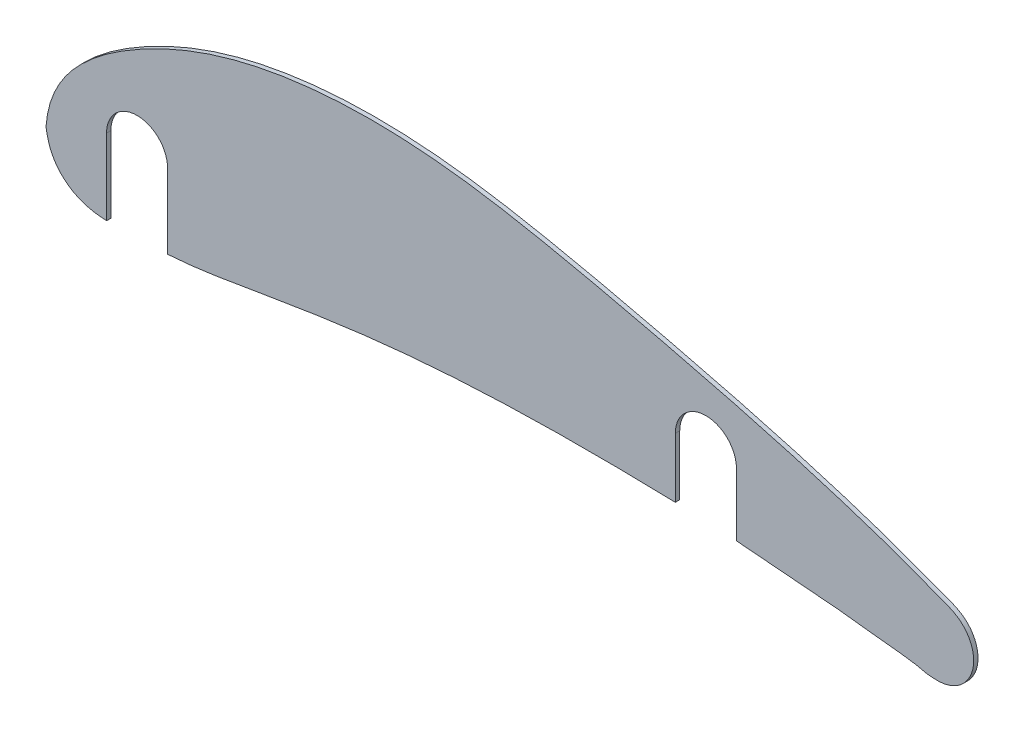
SolidWorks part; units mm, degrees
material "ABS"
ref_plane "Front Plane" through (0, 0, 0) normal (0, 0, 1) x (1, 0, 0)
ref_plane "Top Plane" through (0, 0, 0) normal (0, 1, 0) x (1, 0, 0)
ref_plane "Right Plane" through (0, 0, 0) normal (1, 0, 0) x (0, 0, -1)
sketch "Sketch1" plane through (0, 0, 0) normal (0, 0, 1) x (1, 0, 0)
  spline S0 degree 3 poles (0.0006, 0.0001) (0.8106, 7.3592) (8.6491, 17.8566) (26.2867, 29.9752) (52.1111, 42.0692) (89.5976, 49.2908) (131.4008, 47.8848) (173.2567, 40.0411) (217.9611, 29.613) (256.9521, 19.5289) (290.3598, 8.711) (301.2732, 4.3828) (314.8169, -0.5162) (309.8463, 0.0001) knots 0 0 0 0 0.060864 0.113688 0.188609 0.312909 0.448482 0.557612 0.691544 0.852438 0.929756 0.976058 1 1 1 1
  spline S1 degree 3 poles (309.8463, 0.0001) (303.9568, 1.471) (293.9895, 2.094) (276.264, 4.5144) (260.8463, 5.4274) (235.8588, 7.8703) (205.1014, 8.8381) (157.7186, 9.0307) (110.4973, 6.1815) (66.5062, -0.5867) (36.4547, -6.0985) (15.3166, -6.1891) (1.2307, -6.9241) (0.0006, 0.0001) knots 0 0 0 0 0.057787 0.095275 0.171021 0.205339 0.335319 0.464904 0.658702 0.785512 0.893517 0.943092 1 1 1 1
extrude "Boss-Extrude1" add sketch "Sketch1" along normal blind 1.5875
sketch "Sketch2" plane through (0, 0, 1.5875) normal (0, 0, 1) x (1, 0, 0)
  circle A1 centre (227.2963, 19.0501) radius 5
  circle A2 centre (20.32, 10.16) radius 5
  dimension "D3" = 10
  dimension "D6" = 20.32
  dimension "D8" = 10
  dimension "D1" = 82.55
  dimension "D4" = 19.05
  dimension "D5" = 10.16
extrude "Cut-Extrude1" cut sketch "Sketch2" against normal blind 4 contours A1
sketch "Sketch3" plane through (0, 0, 0) normal (0, 0, -1) x (-1, 0, 0)
  circle A0 centre (-227.2963, 19.0501) radius 5
  circle A1 centre (-20.32, 10.16) radius 5
  circle A2 centre (-227.2963, 19.0501) radius 5 construction
  circle A3 centre (-20.32, 10.16) radius 5 construction
  spline S5 degree 3 poles (-794.819, 3953.6372) (-366.3145, -67.9732) (-338.336, -19.8467) (-305.9476, -12.1233) (-305.5233, -12.0295) (-304.2487, -11.7666) (-303.3965, -11.6156) (-300.8352, -11.213) (-299.1211, -11.0104) (-295.689, -10.6461) (-293.9708, -10.4848) (-291.3954, -10.2247) (-290.5373, -10.1347) (-288.822, -9.9442) (-287.9649, -9.8444) (-285.3941, -9.5376) (-283.6812, -9.3228) (-280.254, -8.9085) (-278.5394, -8.7116) (-273.3892, -8.1853) (-269.9489, -7.9035) (-263.0656, -7.3675) (-259.6226, -7.1135) (-252.7436, -6.5343) (-249.3084, -6.2011) (-242.431, -5.6059) (-238.9878, -5.3542) (-232.0935, -4.9305) (-228.6415, -4.7575) (-218.2859, -4.3276) (-211.3818, -4.1597) (-197.5731, -3.918) (-190.6686, -3.8461) (-176.8592, -3.8453) (-169.9542, -3.9165) (-156.1436, -4.2469) (-149.2349, -4.5055) (-135.4369, -5.2363) (-128.547, -5.7084) (-114.7879, -6.8956) (-107.9189, -7.6126) (-94.2037, -9.3155) (-87.359, -10.2944) (-77.1158, -11.889) (-73.7047, -12.4417) (-66.8874, -13.5783) (-63.482, -14.1674) (-53.262, -15.9097) (-46.4424, -17.0289) (-37.8533, -17.9873) (-36.1323, -18.1567) (-32.6884, -18.4393) (-30.9647, -18.5506) (-25.7891, -18.7998) (-22.3328, -18.8616) (-18.0138, -18.9646) (-17.15, -18.9864) (-15.4226, -19.0355) (-14.559, -19.065) (-12.8314, -19.1079) (-11.9674, -19.1211) (-10.2388, -19.1103) (-9.3743, -19.0865) (-6.8, -18.9358) (-5.1041, -18.7297) (-2.6061, -18.1813) (-1.781, -17.9588) (-0.5569, -17.5549) (-0.1511, -17.4087) (0.6556, -17.0908) (1.0582, -16.9184) (3.0336, -15.9992) (4.4968, -15.0839) (6.1651, -13.6925) (6.4918, -13.4006) (7.122, -12.7971) (7.425, -12.4861) (8.2983, -11.5259) (8.8331, -10.8497) (9.5651, -9.782) (9.7973, -9.4172) (10.2382, -8.6696) (10.4474, -8.2857) (11.035, -7.1145) (11.3705, -6.3152) (11.9375, -4.6822) (12.169, -3.8486) (12.4425, -2.5739) (12.5175, -2.1436) (245.8962, 1311.483) (479.1987, 2624.6798) (712.5006, 3937.874) knots -0.290887 -0.290887 -0.290887 -0.290887 0.003906 0.003906 0.007812 0.007812 0.015625 0.015625 0.03125 0.03125 0.046875 0.046875 0.054687 0.054687 0.0625 0.0625 0.078125 0.078125 0.09375 0.09375 0.125 0.125 0.15625 0.15625 0.1875 0.1875 0.21875 0.21875 0.25 0.25 0.3125 0.3125 0.375 0.375 0.4375 0.4375 0.5 0.5 0.5625 0.5625 0.625 0.625 0.6875 0.6875 0.71875 0.71875 0.75 0.75 0.8125 0.8125 0.828125 0.828125 0.84375 0.84375 0.875 0.875 0.882812 0.882812 0.890625 0.890625 0.898438 0.898438 0.90625 0.90625 0.921875 0.921875 0.929687 0.929687 0.933594 0.933594 0.9375 0.9375 0.953125 0.953125 0.957031 0.957031 0.960938 0.960938 0.96875 0.96875 0.972656 0.972656 0.976563 0.976563 0.984375 0.984375 0.992188 0.992188 0.996094 0.996094 12.93108 12.93108 12.93108 12.93108 only from (-307.6407, -12.5391) to (12.8229, -0.4244)
  spline S6 degree 3 poles (450.4865, -3976.3582) (304.5409, -2650.5224) (158.5953, -1324.6865) (12.5919, 1.6739) (12.5289, 2.1971) (12.2979, 3.7557) (12.0986, 4.783) (11.3667, 7.8296) (10.7001, 9.8139) (9.6458, 12.2364) (9.4233, 12.7191) (8.9589, 13.6734) (8.2345, 15.0856) (7.4307, 16.4423) (5.7262, 19.088) (4.4608, 20.7616) (2.4032, 23.1605) (1.6888, 23.9434) (0.222, 25.4669) (-2.0301, 27.684) (-4.4106, 29.7332) (-9.3168, 33.6415) (-12.7815, 35.993) (-18.1647, 39.2766) (-19.9904, 40.3334) (-23.6661, 42.358) (-25.5203, 43.3273) (-31.1305, 46.109) (-34.9342, 47.7954) (-46.5315, 52.3626) (-54.5152, 54.7412) (-63.7448, 56.7617) (-64.7747, 56.9772) (-66.8348, 57.3892) (-69.9258, 57.9785) (-73.0196, 58.4848) (-79.2106, 59.3934) (-83.3425, 59.8608) (-95.7504, 60.8925) (-104.0386, 61.0863) (-116.492, 60.7375) (-120.6467, 60.5145) (-126.8836, 60.0306) (-128.9634, 59.8445) (-133.1246, 59.4241) (-135.2075, 59.1895) (-145.595, 57.9058) (-153.8328, 56.5247) (-166.1326, 54.1736) (-170.223, 53.3435) (-178.3938, 51.633) (-182.4737, 50.7513) (-194.7, 48.0394) (-202.8328, 46.1427) (-215.0143, 43.2113) (-219.0722, 42.221) (-227.1821, 40.2119) (-231.2322, 39.1918) (-243.362, 36.0642) (-251.4202, 33.8872) (-263.4483, 30.4288) (-267.4479, 29.2444) (-275.4266, 26.8089) (-279.4062, 25.5593) (-285.3572, 23.6252) (-287.3377, 22.9703) (-291.2905, 21.6338) (-293.2629, 20.9523) (-297.195, 19.5486) (-299.1532, 18.8211) (-303.0645, 17.3496) (-305.019, 16.6102) (-307.9551, 15.5148) (-308.9343, 15.1515) (-310.8939, 14.4286) (-311.8752, 14.0719) (-313.8314, 13.3379) (-314.808, 12.9614) (-316.7192, 12.1265) (-317.6523, 11.6639) (-318.978, 10.8209) (-319.4082, 10.5149) (-320.2258, 9.8596) (-320.6153, 9.5093) (-321.3536, 8.7611) (-321.6995, 8.3658) (-322.3367, 7.5434) (-322.6295, 7.1149) (-323.1632, 6.2229) (-323.4044, 5.7588) (-323.8312, 4.7968) (-324.1948, 3.8185) (-324.4364, 2.809) (-324.5716, 2.0401) (-324.6089, 1.7818) (-324.6679, 1.2612) (-324.6896, 0.9981) (-324.7567, -0.3109) (-324.6826, -1.3467) (-324.3823, -2.8833) (-324.249, -3.3956) (-323.9242, -4.3886) (-323.541, -5.3551) (-323.0431, -6.2692) (-322.6256, -6.9348) (-322.4785, -7.1539) (-322.1729, -7.5802) (-322.0142, -7.7878) (-321.1922, -8.7978) (-320.4439, -9.5189) (-318.7612, -10.7826) (-317.8577, -11.3014) (-316.4211, -11.9133) (-315.9254, -12.0903) (-314.9178, -12.3839) (-314.4094, -12.4998) (-313.384, -12.6741) (-312.867, -12.7323) (-311.8251, -12.7968) (-311.2988, -12.8028) (-310.2504, -12.7747) (-309.7275, -12.7412) (-275.8665, -9.8118) (-245.9968, 43.8257) (63.2429, -3989.5034) knots -9.868844 -9.868844 -9.868844 -9.868844 0.003906 0.003906 0.007813 0.007813 0.015625 0.015625 0.03125 0.03125 0.035156 0.035156 0.039063 0.046875 0.046875 0.0625 0.0625 0.070313 0.070313 0.078125 0.09375 0.09375 0.125 0.125 0.140625 0.140625 0.15625 0.15625 0.1875 0.1875 0.25 0.25 0.257813 0.257813 0.265625 0.28125 0.28125 0.3125 0.3125 0.375 0.375 0.40625 0.40625 0.421875 0.421875 0.4375 0.4375 0.5 0.5 0.53125 0.53125 0.5625 0.5625 0.625 0.625 0.65625 0.65625 0.6875 0.6875 0.75 0.75 0.78125 0.78125 0.8125 0.8125 0.828125 0.828125 0.84375 0.84375 0.859375 0.859375 0.875 0.875 0.882813 0.882813 0.890625 0.890625 0.898438 0.898438 0.90625 0.90625 0.910156 0.910156 0.914063 0.914063 0.917969 0.917969 0.921875 0.921875 0.925781 0.925781 0.929688 0.933594 0.933594 0.935547 0.935547 0.9375 0.9375 0.945313 0.945313 0.949219 0.949219 0.953125 0.957031 0.957031 0.958984 0.958984 0.960938 0.960938 0.96875 0.96875 0.976563 0.976563 0.980469 0.980469 0.984375 0.984375 0.988281 0.988281 0.992188 0.992188 0.996094 0.996094 1.245538 1.245538 1.245538 1.245538 only from (12.8229, -0.4244) to (-307.6407, -12.5391)
  spline S7 degree 3 poles (-307.6407, -12.5391) (-307.2176, -12.4334) (-306.7947, -12.3253) (-305.9476, -12.1233) (-305.5233, -12.0295) (-304.2487, -11.7666) (-303.3965, -11.6156) (-300.8352, -11.213) (-299.1211, -11.0104) (-295.689, -10.6461) (-293.9708, -10.4848) (-291.3954, -10.2247) (-290.5373, -10.1347) (-288.822, -9.9442) (-287.9649, -9.8444) (-285.3941, -9.5376) (-283.6812, -9.3228) (-280.254, -8.9085) (-278.5394, -8.7116) (-273.3892, -8.1853) (-269.9489, -7.9035) (-263.0656, -7.3675) (-259.6226, -7.1135) (-252.7436, -6.5343) (-249.3084, -6.2011) (-242.431, -5.6059) (-238.9878, -5.3542) (-232.0935, -4.9305) (-228.6415, -4.7575) (-218.2859, -4.3276) (-211.3818, -4.1597) (-197.5731, -3.918) (-190.6686, -3.8461) (-176.8592, -3.8453) (-169.9542, -3.9165) (-156.1436, -4.2469) (-149.2349, -4.5055) (-135.4369, -5.2363) (-128.547, -5.7084) (-114.7879, -6.8956) (-107.9189, -7.6126) (-94.2037, -9.3155) (-87.359, -10.2944) (-77.1158, -11.889) (-73.7047, -12.4417) (-66.8874, -13.5783) (-63.482, -14.1674) (-53.262, -15.9097) (-46.4424, -17.0289) (-37.8533, -17.9873) (-36.1323, -18.1567) (-32.6884, -18.4393) (-30.9647, -18.5506) (-25.7891, -18.7998) (-22.3328, -18.8616) (-18.0138, -18.9646) (-17.15, -18.9864) (-15.4226, -19.0355) (-14.559, -19.065) (-12.8314, -19.1079) (-11.9674, -19.1211) (-10.2388, -19.1103) (-9.3743, -19.0865) (-6.8, -18.9358) (-5.1041, -18.7297) (-2.6061, -18.1813) (-1.781, -17.9588) (-0.5569, -17.5549) (-0.1511, -17.4087) (0.6556, -17.0908) (1.0582, -16.9184) (3.0336, -15.9992) (4.4968, -15.0839) (6.1651, -13.6925) (6.4918, -13.4006) (7.122, -12.7971) (7.425, -12.4861) (8.2983, -11.5259) (8.8331, -10.8497) (9.5651, -9.782) (9.7973, -9.4172) (10.2382, -8.6696) (10.4474, -8.2857) (11.035, -7.1145) (11.3705, -6.3152) (11.9375, -4.6822) (12.169, -3.8486) (12.4425, -2.5739) (12.5175, -2.1436) (12.6702, -1.284) (12.7465, -0.8542) (12.8229, -0.4244) knots 0 0 0 0 0.003906 0.003906 0.007812 0.007812 0.015625 0.015625 0.03125 0.03125 0.046875 0.046875 0.054687 0.054687 0.0625 0.0625 0.078125 0.078125 0.09375 0.09375 0.125 0.125 0.15625 0.15625 0.1875 0.1875 0.21875 0.21875 0.25 0.25 0.3125 0.3125 0.375 0.375 0.4375 0.4375 0.5 0.5 0.5625 0.5625 0.625 0.625 0.6875 0.6875 0.71875 0.71875 0.75 0.75 0.8125 0.8125 0.828125 0.828125 0.84375 0.84375 0.875 0.875 0.882812 0.882812 0.890625 0.890625 0.898438 0.898438 0.90625 0.90625 0.921875 0.921875 0.929687 0.929687 0.933594 0.933594 0.9375 0.9375 0.953125 0.953125 0.957031 0.957031 0.960938 0.960938 0.96875 0.96875 0.972656 0.972656 0.976563 0.976563 0.984375 0.984375 0.992188 0.992188 0.996094 0.996094 1 1 1 1
  spline S8 degree 3 poles (12.8229, -0.4244) (12.7651, 0.1002) (12.7074, 0.6248) (12.5919, 1.6739) (12.5289, 2.1971) (12.2979, 3.7557) (12.0986, 4.783) (11.3667, 7.8296) (10.7001, 9.8139) (9.6458, 12.2364) (9.4233, 12.7191) (8.9589, 13.6734) (8.2345, 15.0856) (7.4307, 16.4423) (5.7262, 19.088) (4.4608, 20.7616) (2.4032, 23.1605) (1.6888, 23.9434) (0.222, 25.4669) (-2.0301, 27.684) (-4.4106, 29.7332) (-9.3168, 33.6415) (-12.7815, 35.993) (-18.1647, 39.2766) (-19.9904, 40.3334) (-23.6661, 42.358) (-25.5203, 43.3273) (-31.1305, 46.109) (-34.9342, 47.7954) (-46.5315, 52.3626) (-54.5152, 54.7412) (-63.7448, 56.7617) (-64.7747, 56.9772) (-66.8348, 57.3892) (-69.9258, 57.9785) (-73.0196, 58.4848) (-79.2106, 59.3934) (-83.3425, 59.8608) (-95.7504, 60.8925) (-104.0386, 61.0863) (-116.492, 60.7375) (-120.6467, 60.5145) (-126.8836, 60.0306) (-128.9634, 59.8445) (-133.1246, 59.4241) (-135.2075, 59.1895) (-145.595, 57.9058) (-153.8328, 56.5247) (-166.1326, 54.1736) (-170.223, 53.3435) (-178.3938, 51.633) (-182.4737, 50.7513) (-194.7, 48.0394) (-202.8328, 46.1427) (-215.0143, 43.2113) (-219.0722, 42.221) (-227.1821, 40.2119) (-231.2322, 39.1918) (-243.362, 36.0642) (-251.4202, 33.8872) (-263.4483, 30.4288) (-267.4479, 29.2444) (-275.4266, 26.8089) (-279.4062, 25.5593) (-285.3572, 23.6252) (-287.3377, 22.9703) (-291.2905, 21.6338) (-293.2629, 20.9523) (-297.195, 19.5486) (-299.1532, 18.8211) (-303.0645, 17.3496) (-305.019, 16.6102) (-307.9551, 15.5148) (-308.9343, 15.1515) (-310.8939, 14.4286) (-311.8752, 14.0719) (-313.8314, 13.3379) (-314.808, 12.9614) (-316.7192, 12.1265) (-317.6523, 11.6639) (-318.978, 10.8209) (-319.4082, 10.5149) (-320.2258, 9.8596) (-320.6153, 9.5093) (-321.3536, 8.7611) (-321.6995, 8.3658) (-322.3367, 7.5434) (-322.6295, 7.1149) (-323.1632, 6.2229) (-323.4044, 5.7588) (-323.8312, 4.7968) (-324.1948, 3.8185) (-324.4364, 2.809) (-324.5716, 2.0401) (-324.6089, 1.7818) (-324.6679, 1.2612) (-324.6896, 0.9981) (-324.7567, -0.3109) (-324.6826, -1.3467) (-324.3823, -2.8833) (-324.249, -3.3956) (-323.9242, -4.3886) (-323.541, -5.3551) (-323.0431, -6.2692) (-322.6256, -6.9348) (-322.4785, -7.1539) (-322.1729, -7.5802) (-322.0142, -7.7878) (-321.1922, -8.7978) (-320.4439, -9.5189) (-318.7612, -10.7826) (-317.8577, -11.3014) (-316.4211, -11.9133) (-315.9254, -12.0903) (-314.9178, -12.3839) (-314.4094, -12.4998) (-313.384, -12.6741) (-312.867, -12.7323) (-311.8251, -12.7968) (-311.2988, -12.8028) (-310.2504, -12.7747) (-309.7275, -12.7412) (-308.6834, -12.6509) (-308.1621, -12.5933) (-307.6407, -12.5391) knots 0 0 0 0 0.003906 0.003906 0.007813 0.007813 0.015625 0.015625 0.03125 0.03125 0.035156 0.035156 0.039063 0.046875 0.046875 0.0625 0.0625 0.070313 0.070313 0.078125 0.09375 0.09375 0.125 0.125 0.140625 0.140625 0.15625 0.15625 0.1875 0.1875 0.25 0.25 0.257813 0.257813 0.265625 0.28125 0.28125 0.3125 0.3125 0.375 0.375 0.40625 0.40625 0.421875 0.421875 0.4375 0.4375 0.5 0.5 0.53125 0.53125 0.5625 0.5625 0.625 0.625 0.65625 0.65625 0.6875 0.6875 0.75 0.75 0.78125 0.78125 0.8125 0.8125 0.828125 0.828125 0.84375 0.84375 0.859375 0.859375 0.875 0.875 0.882813 0.882813 0.890625 0.890625 0.898438 0.898438 0.90625 0.90625 0.910156 0.910156 0.914063 0.914063 0.917969 0.917969 0.921875 0.921875 0.925781 0.925781 0.929688 0.933594 0.933594 0.935547 0.935547 0.9375 0.9375 0.945313 0.945313 0.949219 0.949219 0.953125 0.957031 0.957031 0.958984 0.958984 0.960938 0.960938 0.96875 0.96875 0.976563 0.976563 0.980469 0.980469 0.984375 0.984375 0.988281 0.988281 0.992188 0.992188 0.996094 0.996094 1 1 1 1
  circle M3 centre (-227.2963, 19.0501) radius 5
  circle M4 centre (-20.32, 10.16) radius 5
  spline M5 degree 3 poles (-309.8463, 0.0001) (-303.9568, 1.471) (-293.9895, 2.094) (-276.264, 4.5144) (-260.8463, 5.4274) (-235.8588, 7.8703) (-205.1014, 8.8381) (-157.7186, 9.0307) (-110.4973, 6.1815) (-66.5062, -0.5867) (-36.4547, -6.0985) (-15.3166, -6.1891) (-1.2307, -6.9241) (-0.0006, 0.0001) knots 0 0 0 0 0.057787 0.095275 0.171021 0.205339 0.335319 0.464904 0.658702 0.785512 0.893517 0.943092 1 1 1 1
  spline M6 degree 3 poles (-0.0006, 0.0001) (-0.8106, 7.3592) (-8.6491, 17.8566) (-26.2867, 29.9752) (-52.1111, 42.0692) (-89.5976, 49.2908) (-131.4008, 47.8848) (-173.2567, 40.0411) (-217.9611, 29.613) (-256.9521, 19.5289) (-290.3598, 8.711) (-301.2732, 4.3828) (-314.8169, -0.5162) (-309.8463, 0.0001) knots 0 0 0 0 0.060864 0.113688 0.188609 0.312909 0.448482 0.557612 0.691544 0.852438 0.929756 0.976058 1 1 1 1
  dimension "D1" = 12.7
extrude "Boss-Extrude2" add sketch "Sketch3" against normal blind 1.5875 contours S7 S8 M5 M6 | M6 M5 M4 M3
sketch "Sketch4" plane through (0, 0, 1.5875) normal (0, 0, 1) x (1, 0, 0)
  line L0 (9.2075, -29.5275) -> (9.2075, 8.5725)
  line L1 (31.4325, 8.5725) -> (31.4325, -29.5275)
  line L2 (31.4325, -29.5275) -> (9.2075, -29.5275)
  line L3 (216.1838, 17.4626) -> (216.1838, -35.7881)
  line L4 (216.1838, -35.7881) -> (238.4088, -35.7881)
  line L5 (238.4088, -35.7881) -> (238.4088, 17.4626)
  arc A0 (216.1838, 17.4626) -> (238.4088, 17.4626) centre (227.2963, 17.4626) cw
  arc A2 (9.2075, 8.5725) -> (31.4325, 8.5725) centre (20.32, 8.5725) cw
  point P9 (227.2963, 19.0501)
  point P10 (227.2963, -35.7881)
  point P12 (227.2963, 28.5751)
  point P13 (20.32, -29.5275)
  point P14 (20.32, 10.16)
  point P16 (20.32, 19.685)
  dimension "D1" = 22.225
  dimension "D2" = 9.525
  dimension "D3" = 53.2507
  dimension "D4" = 22.225
  dimension "D5" = 9.525
  dimension "D6" = 38.1
extrude "Cut-Extrude2" cut sketch "Sketch4" against normal blind 1.5875
